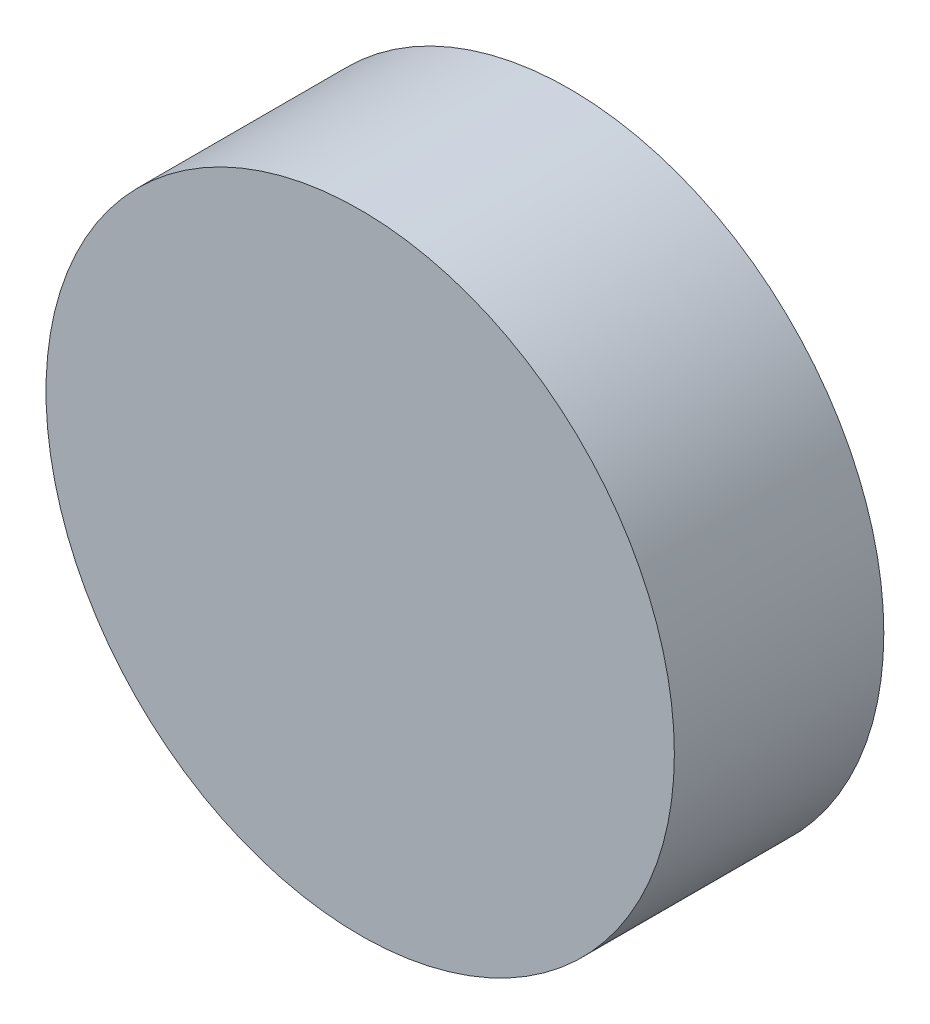
SolidWorks part; units mm, degrees
ref_plane "Front" through (0, 0, 0) normal (0, 0, 1) x (1, 0, 0)
ref_plane "Top" through (0, 0, 0) normal (0, 1, 0) x (1, 0, 0)
ref_plane "Right" through (0, 0, 0) normal (1, 0, 0) x (0, 0, -1)
sketch "Sketch1" plane through (0, 0, 0) normal (0, 0, 1) x (1, 0, 0)
  circle A1 centre (0, 0) radius 38.1
  dimension "D1" = 76.2
extrude "Boss-Extrude1" add sketch "Sketch1" along normal blind 25.4
sketch "Sketch2" plane through (0, 0, 25.4) normal (0, 0, 1) x (1, 0, 0)
  line L0 (0, 0) -> (-24.3219, 20.4085)
  line L1 (0, 0) -> (-15.875, 27.4963)
  line L2 (0, 0) -> (5.5564, 31.5121)
  line L3 (0, 0) -> (15.875, 27.4963)
  line L4 (0, 0) -> (29.8352, 10.8591)
  line L5 (0, 0) -> (31.75, 0)
  line L6 (0, 0) -> (-29.8352, -10.8591)
  line L7 (0, 0) -> (-31.75, 0)
  circle A0 centre (0, 0) radius 31.75 construction
  circle A1 centre (0, 0) radius 38.1 construction
  point P13 (0, 0)
  point P14 (0, 0)
  point P15 (0, 0)
  point P16 (0, 0)
  point P17 (0, 0)
  point P18 (0, 0)
  point P19 (0, 0)
  dimension "D1" = 6.35
  dimension "D2" = 40
  dimension "D3" = 20
  dimension "D4" = 40
  dimension "D5" = 20
  dimension "D6" = 40
  dimension "D7" = 20
  dimension "D8" = 20
equation "\"D8@Sketch2\"=\"D3@Sketch2\""
equation "\"D4@Sketch2\"=\"D2@Sketch2\""
equation "\"D5@Sketch2\"=\"D3@Sketch2\""
equation "\"D6@Sketch2\"=\"D2@Sketch2\""
equation "\"D7@Sketch2\"=\"D3@Sketch2\""
